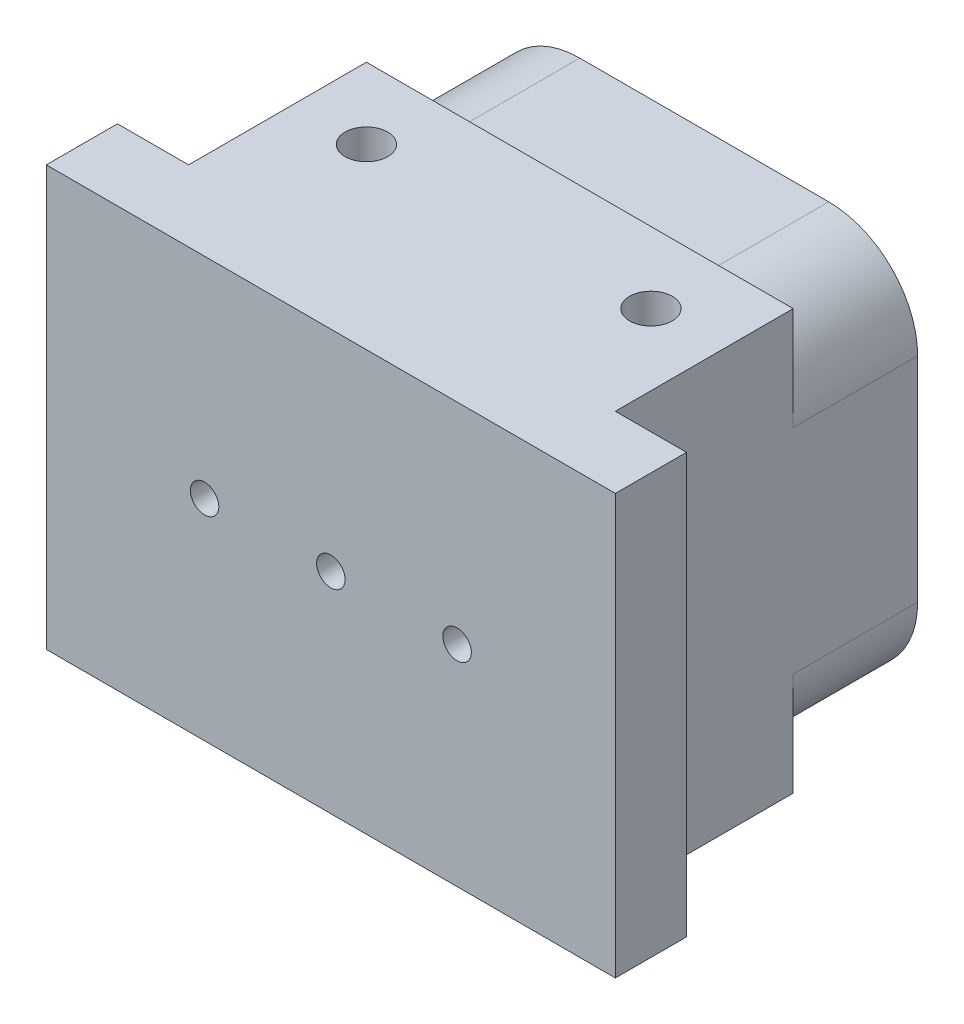
SolidWorks part; units mm, degrees
ref_plane "Front Plane" through (0, 0, 0) normal (0, 0, 1) x (1, 0, 0)
ref_plane "Top Plane" through (0, 0, 0) normal (0, 1, 0) x (1, 0, 0)
ref_plane "Right Plane" through (0, 0, 0) normal (1, 0, 0) x (0, 0, -1)
sketch "Sketch1" plane through (0, 0, 0) normal (0, 1, 0) x (1, 0, 0)
  line L0 (0, 0) -> (8, 0)
  line L1 (8, 0) -> (8, 2)
  line L2 (8, 2) -> (6, 2)
  line L3 (6, 2) -> (6, 7)
  line L8 (6, 7) -> (-6, 7)
  line L9 (-6, 7) -> (-6, 2)
  line L10 (-6, 2) -> (-8, 2)
  line L11 (-8, 2) -> (-8, 0)
  line L12 (-8, 0) -> (0, 0)
  point P15 (0, 7)
  point P16 (0, 7)
  dimension "D1" = 16
  dimension "D2" = 2
  dimension "D5" = 7
  dimension "D6" = 12
extrude "Boss-Extrude1" add sketch "Sketch1" along normal blind 11.8
sketch "Sketch4" plane through (0, 0, 0) normal (0, 0, 1) x (1, 0, 0)
  line L0 (-3.5, 8.9) -> (-3.5, 2.9) construction
  line L2 (-6, 8.9) -> (-6, 2.9)
  line L3 (3.5, 8.9) -> (3.5, 2.9) construction
  line L4 (6, 8.9) -> (6, 2.9)
  line L6 (-3.5, 5.9) -> (3.5, 5.9) construction
  line L7 (-8, 11.8) -> (-8, 0) construction
  line L8 (-3.5, 11.4) -> (3.5, 11.4)
  line L9 (3.5, 0.4) -> (-3.5, 0.4)
  line L10 (-8, 11.8) -> (8, 0) construction
  arc A0 (-3.5, 11.4) -> (-6, 8.9) centre (-3.5, 8.9) ccw
  arc A1 (-6, 2.9) -> (-3.5, 0.4) centre (-3.5, 2.9) ccw
  arc A2 (6, 8.9) -> (3.5, 11.4) centre (3.5, 8.9) ccw
  arc A3 (3.5, 0.4) -> (6, 2.9) centre (3.5, 2.9) ccw
  point P2 (-3, 5.9)
  point P7 (3.5, 5.9)
  point P13 (6, 5.9)
  point P16 (0, 5.9)
  point P19 (-8, 5.9)
  point P27 (0, 11.4)
  dimension "D1" = 2.5
  dimension "D2" = 7
  dimension "D3" = 6
extrude "Boss-Extrude2" add sketch "Sketch4" against normal blind 10.5
sketch "Sketch2" plane through (0, 11.8, 0) normal (0, 1, 0) x (1, 0, 0)
  line L0 (-4, 5) -> (-4, 7) construction
  line L2 (-4, 5) -> (4, 5) construction
  line L3 (4, 5) -> (4, 7) construction
  line L5 (-8, 0) -> (8, 0) construction
  circle A0 centre (-4, 5) radius 0.6
  circle A1 centre (4, 5) radius 0.6
  point P6 (0, 5)
  point P7 (0, 0)
  dimension "D1" = 1.2
  dimension "D2" = 5
  dimension "D3" = 8
extrude "Cut-Extrude1" cut sketch "Sketch2" against normal through all both and the other way through all
sketch "Sketch5" plane through (0, 0, -10.5) normal (0, 0, -1) x (-1, 0, 0)
  line L0 (-3.55, 5.9) -> (8, 5.9) construction
  line L4 (8, 11.8) -> (8, 0) construction
  circle A1 centre (3.55, 5.9) radius 1.625
  circle A4 centre (-3.55, 5.9) radius 1.625
  circle A5 centre (0, 5.9) radius 1.625
  dimension "D1" = 3.25
  dimension "D2" = 7.1
  dimension "D3" = 3.55
extrude "Cut-Extrude2" cut sketch "Sketch5" against normal blind 1.6
sketch "Sketch7" plane through (0, 0, -8.9) normal (0, 0, -1) x (-1, 0, 0)
  circle A1 centre (-3.55, 5.9) radius 0.4
  circle A2 centre (3.55, 5.9) radius 0.4
  circle A4 centre (0, 5.9) radius 0.4
  circle A5 centre (-3.55, 5.9) radius 1.625 construction
  circle A6 centre (0, 5.9) radius 1.625 construction
  dimension "D1" = 0.8
extrude "Cut-Extrude5" cut sketch "Sketch7" against normal through all both and the other way through all
